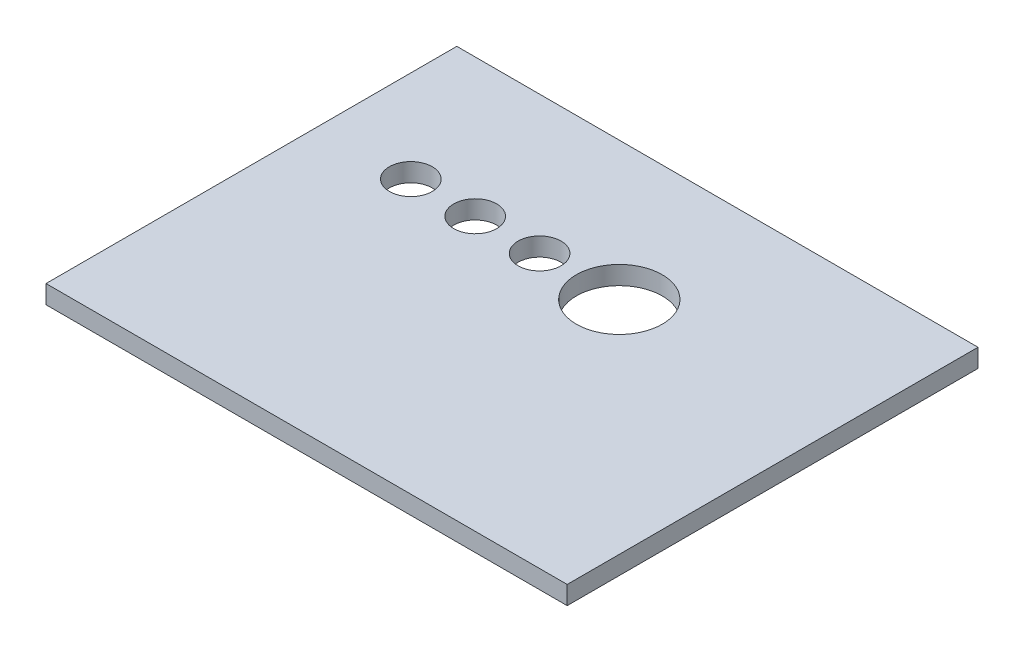
SolidWorks part; units mm, degrees
ref_plane "Front Plane" through (0, 0, 0) normal (0, 0, 1) x (1, 0, 0)
ref_plane "Top Plane" through (0, 0, 0) normal (0, 1, 0) x (1, 0, 0)
ref_plane "Right Plane" through (0, 0, 0) normal (1, 0, 0) x (0, 0, -1)
sketch "Sketch1" plane through (0, 0, 0) normal (0, 1, 0) x (1, 0, 0)
  line L0 (-42.5, 11) -> (42.5, 11) construction
  line L1 (42.5, -33.5) -> (-42.5, -33.5)
  line L2 (42.5, -33.5) -> (42.5, 33.5)
  line L3 (42.5, 33.5) -> (-42.5, 33.5)
  line L4 (-42.5, -33.5) -> (-42.5, 33.5)
  line L5 (42.5, -33.5) -> (-42.5, 33.5) construction
  line L6 (42.5, 33.5) -> (-42.5, -33.5) construction
  circle A4 centre (-27.5, 11) radius 3.5
  circle A5 centre (-17, 11) radius 3.5
  circle A6 centre (-6.5, 11) radius 3.5
  circle A7 centre (6.5, 11) radius 7
  point P0 (0, 0)
  dimension "D4" = 15
  dimension "D7" = 7
  dimension "D8" = 7
  dimension "D9" = 7
  dimension "D11" = 14
  dimension "D1" = 67
  dimension "D2" = 85
  dimension "D3" = 22.5
  dimension "D5" = 10.5
  dimension "D6" = 10.5
  dimension "D10" = 13
extrude "Boss-Extrude1" add sketch "Sketch1" along normal blind 3
